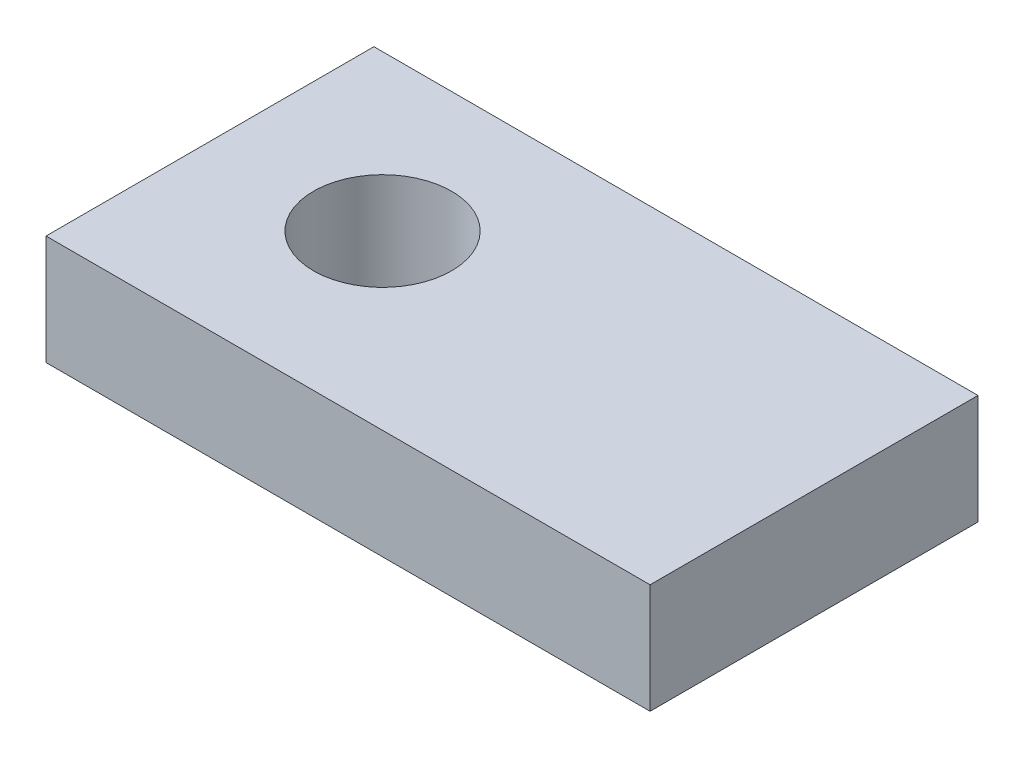
SolidWorks part; units mm, degrees
ref_plane "Piano frontale" through (0, 0, 0) normal (0, 0, 1) x (1, 0, 0)
ref_plane "Piano superiore" through (0, 0, 0) normal (0, 1, 0) x (1, 0, 0)
ref_plane "Piano destro" through (0, 0, 0) normal (1, 0, 0) x (0, 0, -1)
sketch "Schizzo1" plane through (0, 0, 0) normal (0, 1, 0) x (1, 0, 0)
  line L1 (-17.5, -9.5) -> (17.5, -9.5)
  line L2 (-17.5, -9.5) -> (-17.5, 9.5)
  line L3 (-17.5, 9.5) -> (17.5, 9.5)
  line L4 (17.5, -9.5) -> (17.5, 9.5)
  line L5 (-17.5, -9.5) -> (17.5, 9.5) construction
  line L6 (-17.5, 9.5) -> (17.5, -9.5) construction
  circle A0 centre (-8, 0.5) radius 4
  point P0 (0, 0)
  dimension "D3" = 8
  dimension "D1" = 35
  dimension "D2" = 19
  dimension "D4" = 9.5
  dimension "D5" = 10
extrude "Estrusione-Estrusione1" add sketch "Schizzo1" along normal blind 6.35
